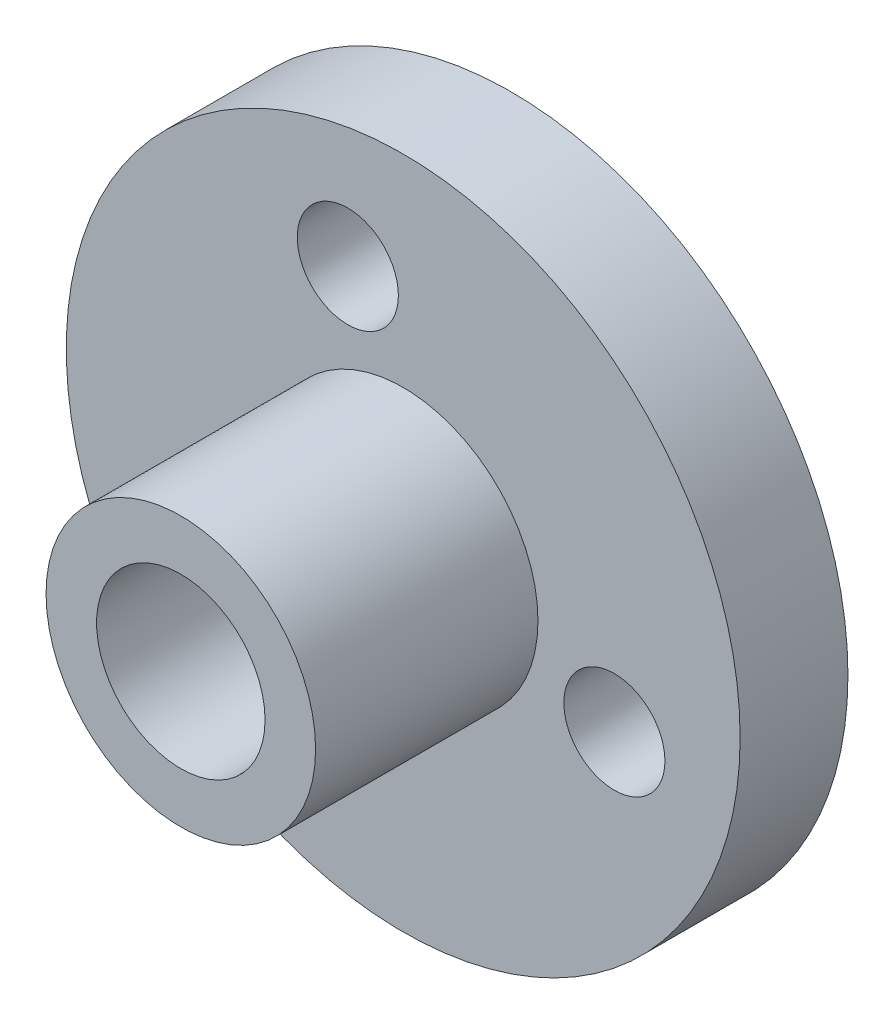
SolidWorks part; units mm, degrees
ref_plane "Plan de face" through (0, 0, 0) normal (0, 0, 1) x (1, 0, 0)
ref_plane "Plan de dessus" through (0, 0, 0) normal (0, 1, 0) x (1, 0, 0)
ref_plane "Plan de droite" through (0, 0, 0) normal (1, 0, 0) x (0, 0, -1)
sketch "Esquisse1" plane through (0, 0, 0) normal (0, 0, 1) x (1, 0, 0)
  circle A0 centre (0, 0) radius 10
  dimension "D1" = 20
extrude "Boss.-Extru.1" add sketch "Esquisse1" along normal blind 3.2
sketch "Esquisse2" plane through (0, 0, 3.2) normal (0, 0, 1) x (1, 0, 0)
  circle A0 centre (0, 0) radius 4
  circle A1 centre (0, 0) radius 10 construction
  dimension "D1" = 8
extrude "Boss.-Extru.2" add sketch "Esquisse2" along normal blind 6.6
sketch "Esquisse3" plane through (0, 0, 3.2) normal (0, 0, 1) x (1, 0, 0)
  circle A0 centre (0, 0) radius 10 construction
  circle A2 centre (-1.6433, 6.2888) radius 1.5
  circle A3 centre (6.2679, -1.7213) radius 1.5
  circle A4 centre (-4.6247, -4.5675) radius 1.5
  point P13 (0, 0)
  dimension "D1" = 6.5
  dimension "D2" = 3
  dimension "D3" = 3
extrude "Enlèv. mat.-Extru.1" cut sketch "Esquisse3" against normal through all
sketch "Esquisse4" plane through (0, 0, 9.8) normal (0, 0, 1) x (1, 0, 0)
  circle A0 centre (0, 0) radius 2.5
  circle A2 centre (0, 0) radius 4 construction
  dimension "D1" = 5
extrude "Enlèv. mat.-Extru.2" cut sketch "Esquisse4" against normal through all
